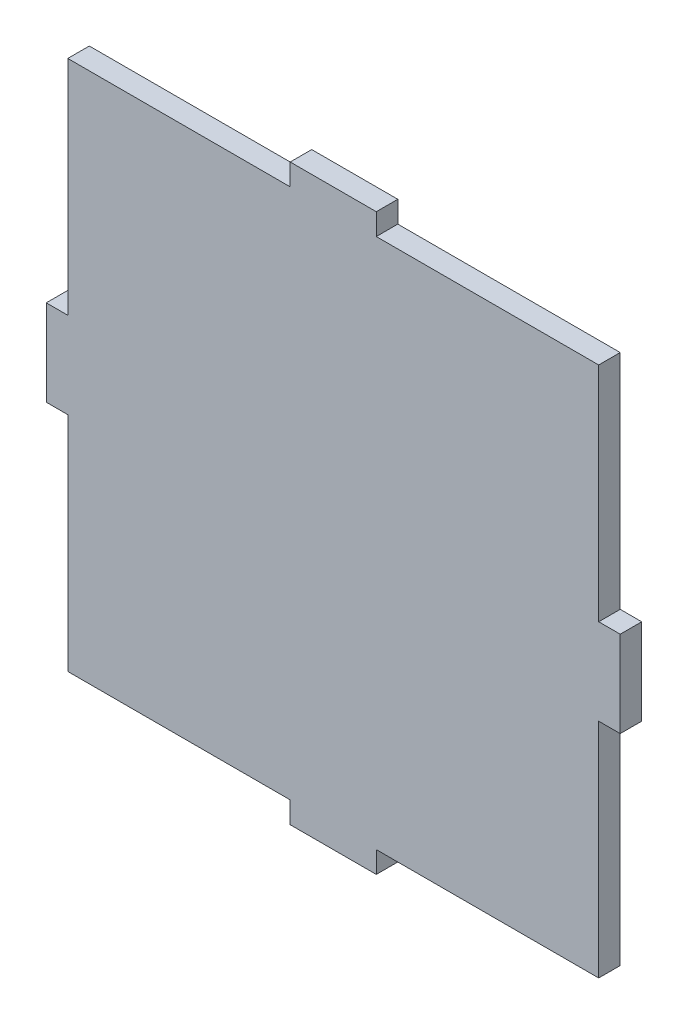
SolidWorks part; units mm, degrees
ref_plane "Plan de face" through (0, 0, 0) normal (0, 0, 1) x (1, 0, 0)
ref_plane "Plan de dessus" through (0, 0, 0) normal (0, 1, 0) x (1, 0, 0)
ref_plane "Plan de droite" through (0, 0, 0) normal (1, 0, 0) x (0, 0, -1)
sketch "Esquisse1" plane through (0, 0, 0) normal (0, 0, 1) x (1, 0, 0)
  line L0 (0, 0) -> (0, 89.7651) construction
  line L1 (0, 0) -> (111.7605, 0) construction
  line L2 (6, 37) -> (37, 37)
  line L3 (37, 37) -> (37, 6)
  line L4 (-6, 40) -> (6, 40)
  line L5 (6, 40) -> (6, 37)
  line L6 (-40, -6) -> (-40, 6)
  line L7 (-37, 6) -> (-40, 6)
  line L8 (-6, 40) -> (-6, 37)
  line L9 (37, 6) -> (40, 6)
  line L10 (40, -6) -> (40, 6)
  line L11 (-37, 37) -> (-37, 6)
  line L12 (-6, 37) -> (-37, 37)
  line L13 (-6, -37) -> (-37, -37)
  line L14 (-37, -37) -> (-37, -6)
  line L15 (37, -6) -> (40, -6)
  line L16 (-6, -40) -> (-6, -37)
  line L17 (-37, -6) -> (-40, -6)
  line L18 (6, -40) -> (6, -37)
  line L19 (-6, -40) -> (6, -40)
  line L20 (37, -37) -> (37, -6)
  line L21 (6, -37) -> (37, -37)
  point P16 (0, 40)
  point P21 (40, 0)
  point P24 (-40, 0)
  point P27 (0, -40)
  dimension "D1" = 37
  dimension "D2" = 6
  dimension "D3" = 6
  dimension "D4" = 3
  dimension "D5" = 3
  dimension "D7" = 37
extrude "Boss.-Extru.1" add sketch "Esquisse1" along normal blind 3
